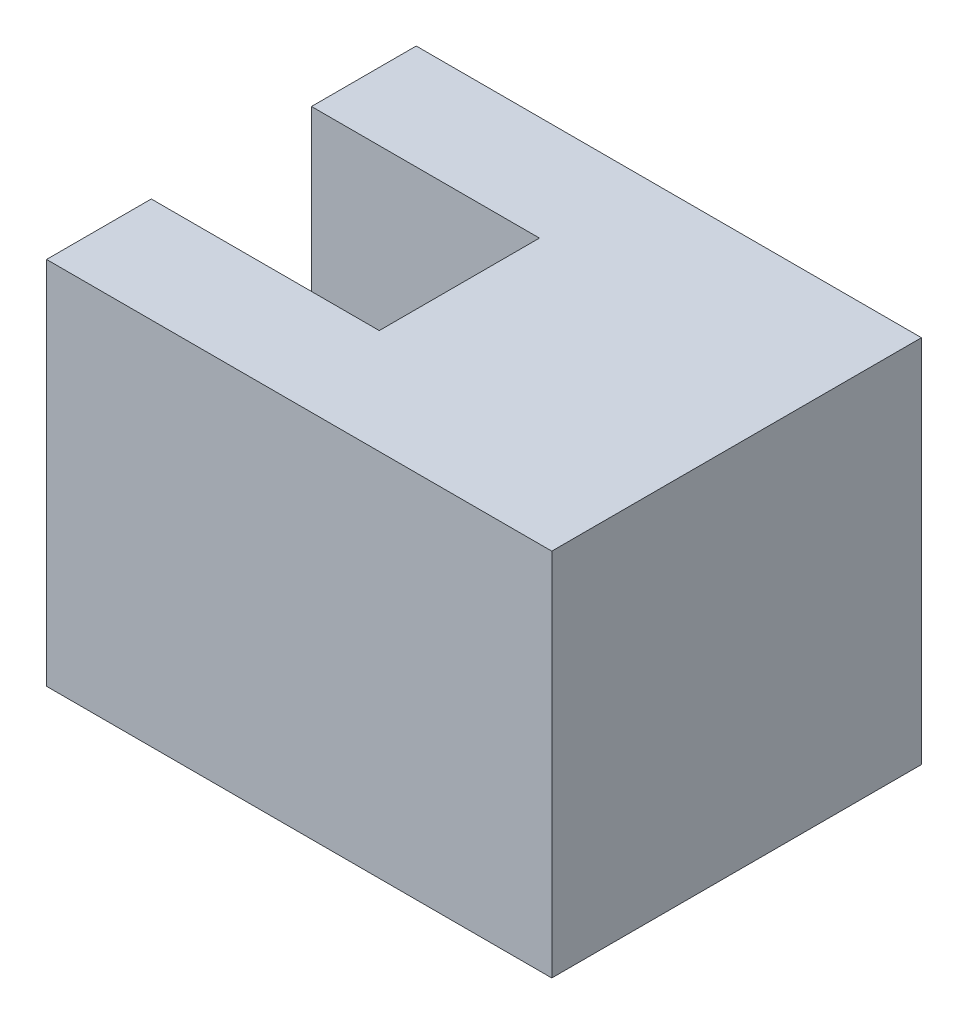
SolidWorks part; units mm, degrees
material "ABS"
ref_plane "Front Plane" through (0, 0, 0) normal (0, 0, 1) x (1, 0, 0)
ref_plane "Top Plane" through (0, 0, 0) normal (0, 1, 0) x (1, 0, 0)
ref_plane "Right Plane" through (0, 0, 0) normal (1, 0, 0) x (0, 0, -1)
sketch "Sketch1" plane through (0, 0, 0) normal (0, 1, 0) x (1, 0, 0)
  line L0 (0, 0) -> (4.1, 0)
  line L1 (4.1, 0) -> (4.1, 3)
  line L2 (4.1, 3) -> (0, 3)
  line L3 (0, 3) -> (0, 2.15)
  line L4 (0, 2.15) -> (1.85, 2.15)
  line L5 (1.85, 2.15) -> (1.85, 0.85)
  line L6 (1.85, 0.85) -> (0, 0.85)
  line L7 (0, 0.85) -> (0, 0)
  dimension "D1" = 3
  dimension "D2" = 4.1
  dimension "D3" = 1.85
  dimension "D4" = 1.3
extrude "Boss-Extrude1" add sketch "Sketch1" along normal blind 3
